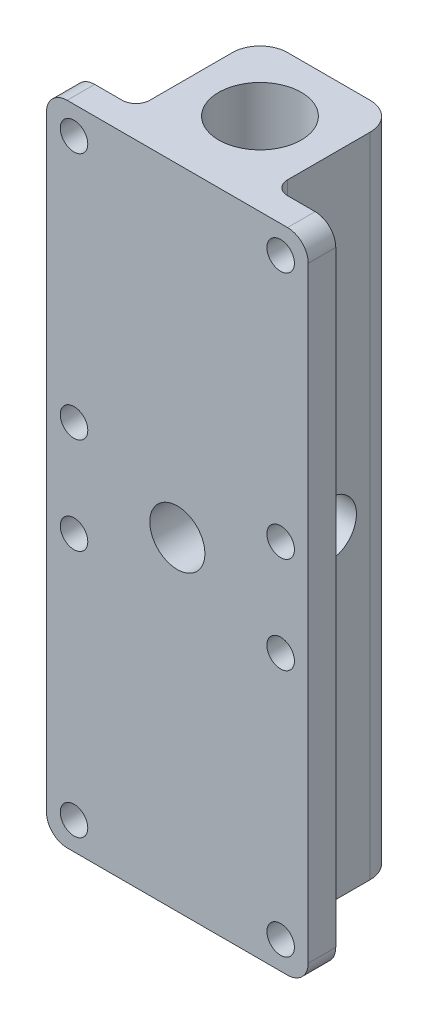
SolidWorks part; units mm, degrees
ref_plane "Front Plane" through (0, 0, 0) normal (0, 0, 1) x (1, 0, 0)
ref_plane "Top Plane" through (0, 0, 0) normal (0, 1, 0) x (1, 0, 0)
ref_plane "Right Plane" through (0, 0, 0) normal (1, 0, 0) x (0, 0, -1)
sketch "Sketch1" plane through (0, 0, 0) normal (0, 0, 1) x (1, 0, 0)
  line L1 (-406.4, 1193.8) -> (406.4, 1193.8)
  line L2 (-482.6, 1117.6) -> (-482.6, -1117.6)
  line L3 (-406.4, -1193.8) -> (406.4, -1193.8)
  line L4 (482.6, 1117.6) -> (482.6, -1117.6)
  line L5 (-482.6, 1193.8) -> (482.6, -1193.8) construction
  line L6 (-482.6, -1193.8) -> (482.6, 1193.8) construction
  arc A0 (406.4, -1193.8) -> (482.6, -1117.6) centre (406.4, -1117.6) ccw
  arc A1 (-482.6, -1117.6) -> (-406.4, -1193.8) centre (-406.4, -1117.6) ccw
  arc A2 (406.4, 1193.8) -> (482.6, 1117.6) centre (406.4, 1117.6) cw
  arc A3 (-406.4, 1193.8) -> (-482.6, 1117.6) centre (-406.4, 1117.6) ccw
  point P0 (0, 0)
  dimension "D3" = 76.2
  dimension "D1" = 2387.6
  dimension "D2" = 965.2
extrude "Boss-Extrude2" add sketch "Sketch1" along normal blind 101.6
sketch "Sketch2" plane through (0, 0, 101.6) normal (0, 0, 1) x (1, 0, 0)
  line L0 (406.4, 1193.8) -> (-406.4, 1193.8) construction
  line L2 (-482.6, 1117.6) -> (-482.6, -1117.6) construction
  line L3 (482.6, -1117.6) -> (482.6, 1117.6) construction
  circle A0 centre (-381, 1092.2) radius 50.8
  circle A1 centre (-381, 177.8) radius 50.8
  circle A2 centre (-381, -177.8) radius 50.8
  circle A3 centre (-381, -1092.2) radius 50.8
  circle A4 centre (381, 1092.2) radius 50.8
  circle A5 centre (381, 177.8) radius 50.8
  circle A6 centre (381, -177.8) radius 50.8
  circle A7 centre (381, -1092.2) radius 50.8
  point P16 (0, 0)
  point P17 (0, 0)
  point P18 (0, 0)
  point P19 (0, 0)
  point P20 (0, 0)
  point P21 (0, 0)
  dimension "D1" = 101.6
  dimension "D2" = 101.6
  dimension "D3" = 914.4
  dimension "D4" = 355.6
  dimension "D5" = 914.4
  dimension "D6" = 101.6
  dimension "D7" = 101.6
extrude "Cut-Extrude1" cut sketch "Sketch2" against normal through all
sketch "Sketch3" plane through (0, 1193.8, 0) normal (0, 1, 0) x (1, 0, 0)
  line L0 (-254, 0) -> (254, 0)
  line L1 (406.4, 0) -> (-406.4, 0) construction
  line L2 (254, 0) -> (254, 355.6)
  line L3 (152.4, 457.2) -> (-152.4, 457.2)
  line L4 (-254, 355.6) -> (-254, 0)
  arc A0 (152.4, 457.2) -> (254, 355.6) centre (152.4, 355.6) cw
  arc A1 (-152.4, 457.2) -> (-254, 355.6) centre (-152.4, 355.6) ccw
  circle A2 centre (0, 203.2) radius 152.4
  point P5 (0, 0)
  point P11 (254, 457.2)
  point P14 (-254, 457.2)
  dimension "D3" = 101.6
  dimension "D4" = 304.8
  dimension "D1" = 457.2
  dimension "D2" = 508
  dimension "D5" = 203.2
  dimension "D6" = 254
extrude "Boss-Extrude3" add sketch "Sketch3" against normal up to surface (2387.6 mm away) up to face at (0, -1193.8, 50.8)
fillet "Fillet1" radius 50.8 2 edges at (-254, 0, 0) (254, 0, 0)
sketch "Sketch4" plane through (0, 0, -457.2) normal (0, 0, -1) x (-1, 0, 0)
  line L0 (0, 1292.5766) -> (0, -1292.5766) construction
  line L1 (152.4, -1193.8) -> (-152.4, -1193.8) construction
  circle A0 centre (0, 0) radius 101.6
  point P4 (0, 0)
  dimension "D1" = 203.2
  dimension "D2" = 1193.8
extrude "Cut-Extrude2" cut sketch "Sketch4" against normal through all
sketch "Sketch5" plane through (-254, 0, 0) normal (-1, 0, 0) x (0, 0, 1)
  line L0 (-50.8, -1193.8) -> (-355.6, -1193.8) construction
  line L3 (-355.6, 1193.8) -> (-50.8, 1193.8) construction
  circle A0 centre (-203.2, 0) radius 101.6
  dimension "D1" = 203.2
  dimension "D2" = 1193.8
  dimension "D3" = 152.4
extrude "Cut-Extrude3" cut sketch "Sketch5" against normal through all
